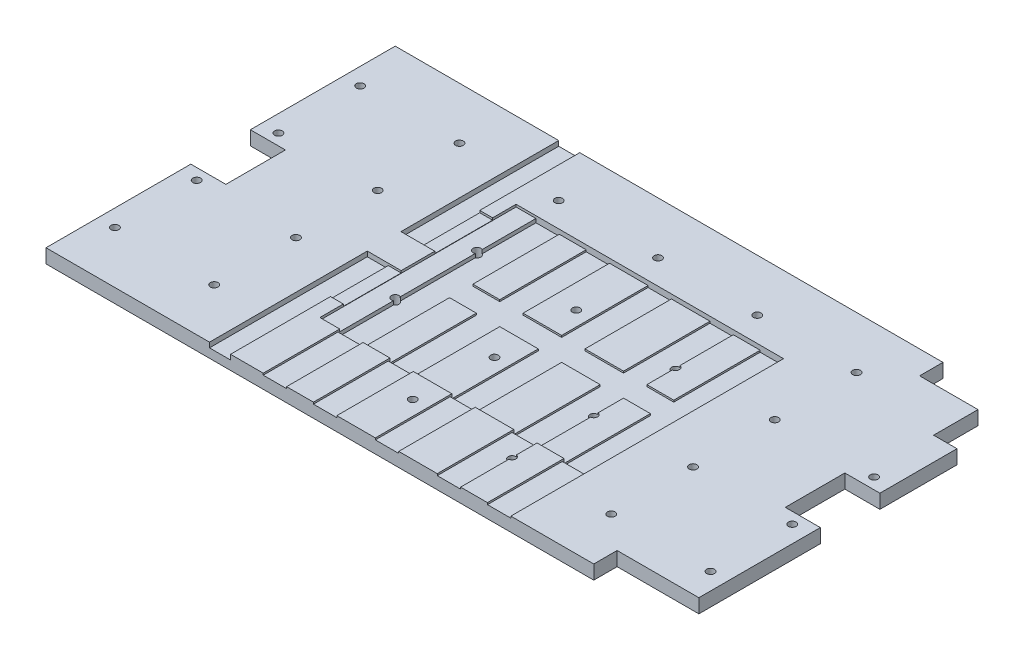
SolidWorks part; units mm, degrees
ref_plane "Front Plane" through (0, 0, 0) normal (0, 0, 1) x (1, 0, 0)
ref_plane "Top Plane" through (0, 0, 0) normal (0, 1, 0) x (1, 0, 0)
ref_plane "Right Plane" through (0, 0, 0) normal (1, 0, 0) x (0, 0, -1)
sketch "Sketch1" plane through (0, 0, 0) normal (0, 1, 0) x (1, 0, 0)
  line L1 (269.5, -149.5) -> (-269.5, -149.5)
  line L2 (269.5, -149.5) -> (269.5, 149.5)
  line L3 (269.5, 149.5) -> (-269.5, 149.5)
  line L4 (-269.5, -149.5) -> (-269.5, 149.5)
  line L5 (269.5, -149.5) -> (-269.5, 149.5) construction
  line L6 (269.5, 149.5) -> (-269.5, -149.5) construction
  point P0 (0, 0)
  dimension "D1" = 299
  dimension "D2" = 539
extrude "Boss-Extrude1" add sketch "Sketch1" against normal blind 12
sketch "Sketch15" plane through (0, 0, 0) normal (0, 1, 0) x (1, 0, 0)
  line L0 (269.5, 149.5) -> (199.5, 149.5)
  line L1 (269.5, 149.5) -> (-269.5, 149.5) construction
  line L2 (199.5, 149.5) -> (199.5, 129.5)
  line L3 (199.5, 129.5) -> (249.5, 129.5)
  line L4 (249.5, 129.5) -> (249.5, 91.5)
  line L5 (249.5, 91.5) -> (269.5, 91.5)
  line L6 (269.5, -149.5) -> (269.5, 149.5) construction
  line L7 (269.5, 91.5) -> (269.5, 149.5)
  line L8 (269.5, -149.5) -> (199.5, -149.5)
  line L9 (-269.5, -149.5) -> (269.5, -149.5) construction
  line L10 (199.5, -149.5) -> (199.5, -129.5)
  line L11 (199.5, -129.5) -> (269.5, -129.5)
  line L12 (269.5, -129.5) -> (269.5, -149.5)
  dimension "D1" = 20
  dimension "D2" = 20
  dimension "D3" = 20
  dimension "D4" = 70
  dimension "D5" = 70
  dimension "D6" = 58
extrude "Cut-Extrude8" cut sketch "Sketch15" against normal through all
sketch "Sketch2" plane through (0, 0, 0) normal (0, 1, 0) x (1, 0, 0)
  line L0 (-269.5, 0) -> (269.5, 0) construction
  line L1 (-269.5, 149.5) -> (-269.5, -149.5) construction
  line L4 (-269.5, -25.5) -> (-239.5, -25.5)
  line L5 (-269.5, -25.5) -> (-269.5, 25.5)
  line L6 (-269.5, 25.5) -> (-239.5, 25.5)
  line L7 (-239.5, -25.5) -> (-239.5, 25.5)
  point P10 (-269.5, 0)
  dimension "D1" = 51
  dimension "D2" = 30
extrude "Cut-Extrude1" cut sketch "Sketch2" against normal through all
mirror "Mirror1" about plane through (0, 0, 0) normal (1, 0, 0) of "Cut-Extrude1"
sketch "cell" plane through (0, 0, 0) normal (0, 1, 0) x (1, 0, 0)
  line L12 (-100.5, 62.4) -> (-129.5, 62.4)
  line L13 (-129.5, 62.4) -> (-129.5, 15.9)
  line L14 (-129.5, 15.9) -> (-100.5, 15.9)
  line L15 (-100.5, 15.9) -> (-100.5, -15.9)
  line L16 (-100.5, -15.9) -> (-129.5, -15.9)
  line L17 (-129.5, -15.9) -> (-129.5, -62.4)
  line L18 (-129.5, -62.4) -> (-100.5, -62.4)
  line L19 (-100.5, -62.4) -> (-100.5, -84)
  line L20 (-100.5, -84) -> (128.5, -84)
  line L21 (128.5, -84) -> (128.5, 84)
  line L22 (128.5, 84) -> (-100.5, 84)
  line L23 (-100.5, 84) -> (-100.5, 62.4)
  line L24 (-100.5, 62.4) -> (-129.5, 62.4)
  line L25 (-129.5, 62.4) -> (-129.5, 15.9)
  line L26 (-129.5, 15.9) -> (-100.5, 15.9)
  line L27 (-100.5, 15.9) -> (-100.5, -15.9)
  line L28 (-100.5, -15.9) -> (-129.5, -15.9)
  line L29 (-129.5, -15.9) -> (-129.5, -62.4)
  line L30 (-129.5, -62.4) -> (-100.5, -62.4)
  line L31 (-100.5, -62.4) -> (-100.5, -84)
  line L32 (-100.5, -84) -> (128.5, -84)
  line L33 (128.5, -84) -> (128.5, 84)
  line L34 (128.5, 84) -> (-100.5, 84)
  line L35 (-100.5, 84) -> (-100.5, 62.4)
  dimension "D1" = 0
sketch "Sketch4" plane through (0, 0, 0) normal (0, 1, 0) x (1, 0, 0)
  line L0 (128.5, 84) -> (-100.5, 84) construction
  line L1 (128.5, -84) -> (128.5, 84) construction
  line L2 (-100.5, -84) -> (128.5, -84) construction
  line L3 (128.5, 84) -> (-100.5, 84)
  line L4 (128.5, -84) -> (128.5, 84)
  line L5 (-100.5, -84) -> (128.5, -84)
  line L6 (-100.5, 84) -> (-100.5, -84)
extrude "Cut-Extrude2" cut sketch "Sketch4" against normal blind 3.75
sketch "Sketch5" plane through (0, 0, 0) normal (0, 1, 0) x (1, 0, 0)
  line L0 (-129.5, 149.5) -> (-129.5, -149.5)
  line L1 (-129.5, -149.5) -> (-111.5, -149.5)
  line L2 (-111.5, -149.5) -> (-111.5, 149.5)
  line L3 (-111.5, 149.5) -> (-129.5, 149.5)
  line L5 (-129.5, -62.4) -> (-129.5, -15.9) construction
  line L6 (-129.5, 15.9) -> (-129.5, 62.4) construction
  line L7 (-269.5, -149.5) -> (199.5, -149.5) construction
  line L8 (199.5, 149.5) -> (-269.5, 149.5) construction
  line L9 (-129.5, -62.4) -> (-129.5, -15.9) construction
  line L10 (-129.5, 15.9) -> (-129.5, 62.4) construction
  point P0 (-129.5, -62.4)
  dimension "D1" = 18
extrude "Cut-Extrude3" cut sketch "Sketch5" against normal blind 4.25
sketch "Sketch6" plane through (0, 0, 0) normal (0, 1, 0) x (1, 0, 0)
  line L0 (-111.5, 63.9) -> (-100.5, 63.9)
  line L1 (-111.5, -149.5) -> (-111.5, 149.5) construction
  line L2 (-100.5, 84) -> (-100.5, 62.4) construction
  line L3 (-111.5, 14.4) -> (-100.5, 14.4)
  line L4 (-100.5, 15.9) -> (-100.5, -15.9) construction
  line L5 (-111.5, -14.4) -> (-100.5, -14.4)
  line L6 (-111.5, -149.5) -> (-111.5, 149.5) construction
  line L7 (-111.5, -63.9) -> (-100.5, -63.9)
  line L8 (-100.5, -62.4) -> (-100.5, -84) construction
  line L9 (-100.5, 62.4) -> (-129.5, 62.4) construction
  line L10 (-129.5, 15.9) -> (-100.5, 15.9) construction
  line L11 (-100.5, -15.9) -> (-129.5, -15.9) construction
  line L12 (-129.5, -62.4) -> (-100.5, -62.4) construction
  line L13 (-111.5, 63.9) -> (-111.5, 14.4)
  line L14 (-100.5, 63.9) -> (-100.5, 14.4)
  line L15 (-111.5, -14.4) -> (-111.5, -63.9)
  line L16 (-100.5, -14.4) -> (-100.5, -63.9)
  dimension "D1" = 1.5
  dimension "D2" = 1.5
  dimension "D3" = 1.5
  dimension "D4" = 1.5
extrude "Cut-Extrude4" cut sketch "Sketch6" against normal blind 1.75
sketch "Sketch7" plane through (0, -3.75, 0) normal (0, 1, 0) x (1, 0, 0)
  line L0 (-100.5, -84) -> (128.5, -84) construction
  line L1 (-100.5, 84) -> (-83.5, 84)
  line L2 (-100.5, 84) -> (-100.5, -84)
  line L3 (-100.5, -84) -> (-83.5, -84)
  line L4 (-83.5, 84) -> (-83.5, -84)
  dimension "D1" = 17
extrude "Boss-Extrude3" add sketch "Sketch7" along normal blind 1.7
sketch "Sketch8" plane through (0, -12, 0) normal (0, -1, 0) x (1, 0, 0)
  point P0 (-255, 105)
  point P1 (-170, 105)
  point P5 (-85, 105)
  point P6 (0, 105)
  point P7 (85, 105)
  point P8 (170, 105)
  point P9 (255, 105)
  point P10 (-170, 35)
  point P11 (-85, 35)
  point P12 (0, 35)
  point P13 (85, 35)
  point P14 (170, 35)
  point P15 (255, 35)
  point P16 (-170, -35)
  point P17 (-85, -35)
  point P18 (0, -35)
  point P19 (85, -35)
  point P20 (170, -35)
  point P21 (255, -35)
  point P22 (-170, -105)
  point P23 (-85, -105)
  point P24 (0, -105)
  point P25 (85, -105)
  point P26 (170, -105)
  point P27 (255, -105)
  point P28 (-255, 35)
  point P29 (-255, -35)
  point P30 (-255, -105)
  dimension "D1" = 255
  dimension "D2" = 105
  dimension "D3" = 7
  dimension "D4" = 4
hole_wizard "M6 Clearance Hole1" positions "3DSketch1" profile "Sketch9" hole size "M6" standard "ANSI Metric" end condition through all
sketch3d "3DSketch1"
  point P0 (-255, -12, 105)
  point P3 (-255, -12, 35)
  point P6 (-255, -12, -105)
  point P9 (-255, -12, -35)
  point P12 (-170, -12, -105)
  point P15 (-170, -12, -35)
  point P18 (-170, -12, 35)
  point P21 (-170, -12, 105)
  point P27 (0, -12, 105)
  point P30 (85, -12, 105)
  point P33 (170, -12, 105)
  point P36 (255, -12, 105)
  point P39 (255, -12, 35)
  point P42 (170, -12, 35)
  point P45 (85, -12, 35)
  point P48 (0, -12, 35)
  point P51 (-85, -12, 35)
  point P54 (-85, -12, -35)
  point P57 (0, -12, -35)
  point P60 (85, -12, -35)
  point P63 (170, -12, -35)
  point P66 (255, -12, -35)
  point P72 (170, -12, -105)
  point P75 (85, -12, -105)
  point P78 (0, -12, -105)
  point P81 (-85, -12, -105)
sketch "Sketch9" plane through (-255, -12, 105) normal (1, 0, 0) x (0, 0, -1)
  line L0 (0, 0) -> (0, 12)
  line L1 (0, 12) -> (3.3, 12)
  line L2 (3.3, 12) -> (3.3, 0)
  line L5 (3.3, 0) -> (0, 0)
  line L11 (0, -6.35) -> (0, 107.95) construction
  dimension "Thru Hole Dia." = 6.6
  dimension "Thru Hole Depth" = 12
sketch "Sketch10" plane through (0, -4.25, 0) normal (0, 1, 0) x (1, 0, 0)
  line L0 (-129.5, 149.5) -> (-129.5, -149.5) construction
  line L1 (-111.5, 14.4) -> (-129.5, 14.4)
  line L2 (-111.5, 14.4) -> (-111.5, -14.4)
  line L3 (-111.5, -14.4) -> (-129.5, -14.4)
  line L4 (-129.5, 14.4) -> (-129.5, -14.4)
  line L5 (-100.5, -14.4) -> (-111.5, -14.4) construction
extrude "Boss-Extrude4" add sketch "Sketch10" along normal up to surface (4.25 mm away) up to face at (-255, 0, 101.7)
sketch "Sketch11" plane through (0, 0, 0) normal (0, 1, 0) x (1, 0, 0)
  line L0 (-83.5, 84) -> (128.5, 84) construction
  line L1 (22.5, 84) -> (22.5, -84) construction
  line L2 (-83.5, -84) -> (128.5, -84) construction
  line L3 (22.5, -84) -> (128.5, -84) construction
  line L4 (75.5, -84) -> (75.5, 84) construction
  line L5 (22.5, -84) -> (-83.5, -84) construction
  line L6 (-30.5, -84) -> (-30.5, 84) construction
  line L7 (118.5, 0) -> (-83.5, 0) construction
  line L8 (-83.5, -32.0606) -> (-83.5, 32.0606) construction
  line L9 (-73.5, 84) -> (-73.5, -84) construction
  line L10 (118.5, 84) -> (118.5, -84) construction
  line L11 (-83.5, -84) -> (-83.5, -37.9394) construction
  line L12 (128.5, -84) -> (128.5, 84) construction
  dimension "D1" = 10
  dimension "D2" = 10
sketch "Sketch12" plane through (0, -3.75, 0) normal (0, 1, 0) x (1, 0, 0)
  line L0 (32.5, -10) -> (32.5, -84)
  line L1 (65.5, 10) -> (65.5, 84)
  line L2 (-83.5, 84) -> (-83.5, -84)
  line L3 (-83.5, 84) -> (-83.5, -84)
  line L4 (-63.5, 84) -> (-63.5, -84)
  line L5 (-63.5, 84) -> (-63.5, 10)
  line L6 (65.5, -10) -> (32.5, -10)
  line L7 (-20.5, -84) -> (-20.5, 84)
  line L8 (-20.5, -84) -> (-20.5, -10)
  line L9 (-40.5, -84) -> (-40.5, 84)
  line L10 (-40.5, -84) -> (-40.5, -10)
  line L11 (85.5, 10) -> (85.5, 84)
  line L12 (12.5, 84) -> (12.5, -84)
  line L13 (12.5, 84) -> (12.5, 10)
  line L14 (32.5, 84) -> (32.5, -84)
  line L15 (32.5, 84) -> (32.5, 10)
  line L16 (108.5, -10) -> (108.5, -84)
  line L17 (85.5, -84) -> (85.5, 84)
  line L18 (85.5, -84) -> (85.5, -10)
  line L19 (65.5, -84) -> (65.5, 84)
  line L20 (65.5, -84) -> (65.5, -10)
  line L21 (65.5, 10) -> (32.5, 10)
  line L22 (108.5, 84) -> (108.5, -84)
  line L23 (108.5, 84) -> (108.5, 10)
  line L24 (128.5, 84) -> (128.5, -84)
  line L25 (128.5, 84) -> (128.5, -84)
  line L26 (-83.5, 84) -> (-63.5, 84)
  line L27 (118.5, 10) -> (-83.5, 10)
  line L28 (108.5, 10) -> (85.5, 10)
  line L29 (118.5, -10) -> (-83.5, -10)
  line L30 (108.5, -10) -> (85.5, -10)
  line L31 (-40.5, 84) -> (-20.5, 84)
  line L32 (12.5, 84) -> (32.5, 84)
  line L33 (65.5, 84) -> (85.5, 84)
  line L34 (128.5, 84) -> (108.5, 84)
  line L35 (128.5, -84) -> (108.5, -84)
  line L36 (85.5, -84) -> (65.5, -84)
  line L37 (32.5, -84) -> (12.5, -84)
  line L38 (-20.5, -84) -> (-40.5, -84)
  line L39 (-63.5, -84) -> (-83.5, -84)
  line L40 (-63.5, -10) -> (-63.5, -84)
  line L41 (-40.5, 10) -> (-40.5, 84)
  line L42 (-40.5, -10) -> (-63.5, -10)
  line L43 (-20.5, 10) -> (-20.5, 84)
  line L44 (12.5, -10) -> (12.5, -84)
  line L45 (12.5, -10) -> (-20.5, -10)
  line L46 (12.5, 10) -> (-20.5, 10)
  line L47 (-40.5, 10) -> (-63.5, 10)
  dimension "D1" = 10
  dimension "D2" = 10
  dimension "D3" = 10
  dimension "D4" = 10
  dimension "D5" = 10
  dimension "D6" = 10
  dimension "D7" = 10
  dimension "D8" = 10
  dimension "D9" = 10
  dimension "D10" = 10
  dimension "D11" = 10
  dimension "D12" = 10
extrude "Cut-Extrude5" cut sketch "Sketch12" against normal blind 1.5
sketch "Sketch13" plane through (0, 0, 0) normal (0, 1, 0) x (1, 0, 0)
  line L0 (-63.5, -84) -> (-63.5, -10) construction
  line L1 (-83.5, -84) -> (-63.5, -84)
  line L2 (-83.5, -84) -> (-83.5, -85.5)
  line L3 (-83.5, -85.5) -> (-63.5, -85.5)
  line L4 (-63.5, -84) -> (-63.5, -85.5)
  line L5 (-40.5, -84) -> (-20.5, -84)
  line L6 (-40.5, -84) -> (-40.5, -85.5)
  line L7 (-40.5, -85.5) -> (-20.5, -85.5)
  line L8 (-20.5, -84) -> (-20.5, -85.5)
  line L9 (12.5, -84) -> (32.5, -84)
  line L10 (12.5, -84) -> (12.5, -85.5)
  line L11 (12.5, -85.5) -> (32.5, -85.5)
  line L12 (32.5, -84) -> (32.5, -85.5)
  line L13 (65.5, -84) -> (85.5, -84)
  line L14 (65.5, -84) -> (65.5, -85.5)
  line L15 (65.5, -85.5) -> (85.5, -85.5)
  line L16 (85.5, -84) -> (85.5, -85.5)
  line L17 (108.5, -84) -> (128.5, -84)
  line L18 (108.5, -84) -> (108.5, -85.5)
  line L19 (108.5, -85.5) -> (128.5, -85.5)
  line L20 (128.5, -84) -> (128.5, -85.5)
  line L21 (-20.5, -84) -> (-20.5, -10) construction
  line L22 (32.5, -84) -> (32.5, -10) construction
  line L23 (85.5, -84) -> (85.5, -38.2619) construction
  line L24 (128.5, -84) -> (128.5, 84) construction
  dimension "D1" = 1.5
extrude "Cut-Extrude6" cut sketch "Sketch13" against normal up to surface (5.25 mm away) up to face at (18.5, -5.25, 0)
sketch "Sketch14" plane through (0, 0, 0) normal (0, 1, 0) x (1, 0, 0)
  line L0 (-111.5, -149.5) -> (199.5, -149.5) construction
  line L1 (-83.5, -85.5) -> (-63.5, -85.5)
  line L2 (-83.5, -85.5) -> (-83.5, -149.5)
  line L3 (-83.5, -149.5) -> (-63.5, -149.5)
  line L4 (-63.5, -85.5) -> (-63.5, -149.5)
  line L5 (-63.5, -85.5) -> (-63.5, -10) construction
  line L6 (-40.5, -85.5) -> (-20.5, -85.5)
  line L7 (-40.5, -85.5) -> (-40.5, -149.5)
  line L8 (-40.5, -149.5) -> (-20.5, -149.5)
  line L9 (-20.5, -85.5) -> (-20.5, -149.5)
  line L10 (12.5, -85.5) -> (32.5, -85.5)
  line L11 (12.5, -85.5) -> (12.5, -149.5)
  line L12 (12.5, -149.5) -> (32.5, -149.5)
  line L13 (32.5, -85.5) -> (32.5, -149.5)
  line L14 (65.5, -85.5) -> (85.5, -85.5)
  line L15 (65.5, -85.5) -> (65.5, -149.5)
  line L16 (65.5, -149.5) -> (85.5, -149.5)
  line L17 (85.5, -85.5) -> (85.5, -149.5)
  line L18 (108.5, -85.5) -> (128.5, -85.5)
  line L19 (108.5, -85.5) -> (108.5, -149.5)
  line L20 (108.5, -149.5) -> (128.5, -149.5)
  line L21 (128.5, -85.5) -> (128.5, -149.5)
  line L22 (-20.5, -85.5) -> (-20.5, -10) construction
  line L23 (32.5, -85.5) -> (32.5, -10) construction
  line L24 (85.5, -84) -> (85.5, -38.2619) construction
  line L25 (128.5, -85.5) -> (128.5, 84) construction
extrude "Cut-Extrude7" cut sketch "Sketch14" against normal blind 1.5
